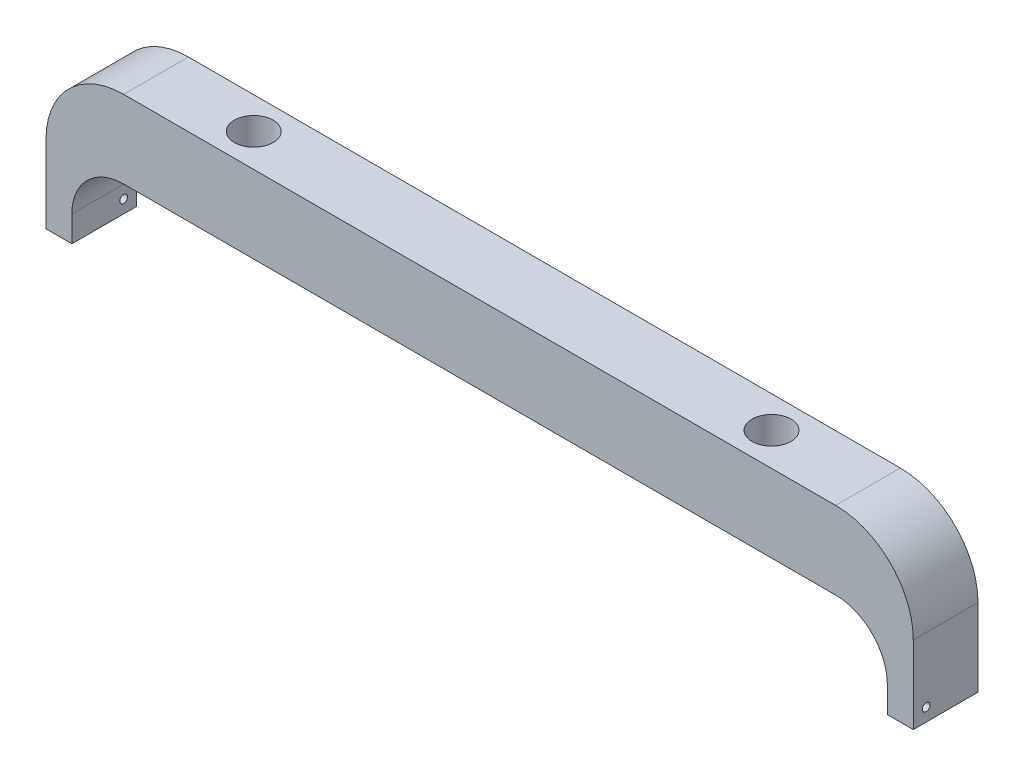
SolidWorks part; units mm, degrees
ref_plane "Front Plane" through (0, 0, 0) normal (0, 0, 1) x (1, 0, 0)
ref_plane "Top Plane" through (0, 0, 0) normal (0, 1, 0) x (1, 0, 0)
ref_plane "Right Plane" through (0, 0, 0) normal (1, 0, 0) x (0, 0, -1)
sketch "Sketch2" plane through (0, 0, 0) normal (0, 0, 1) x (1, 0, 0)
  line L0 (-27.5, 0) -> (-27.5, -6)
  line L1 (-27.5, 0) -> (27.5, 0)
  line L2 (-27.5, -6) -> (27.5, -6)
  line L3 (27.5, -6) -> (27.5, 0)
  line L4 (-33.5, -6) -> (-33.5, -12)
  line L5 (-33.5, -12) -> (-31.5, -12)
  line L6 (33.5, -6) -> (33.5, -12)
  line L7 (33.5, -12) -> (31.5, -12)
  line L8 (-31.5, -12) -> (-31.5, -10)
  line L10 (31.5, -12) -> (31.5, -10)
  arc A0 (-27.5, 0) -> (-33.5, -6) centre (-27.5, -6) ccw
  arc A1 (27.5, 0) -> (33.5, -6) centre (27.5, -6) cw
  arc A2 (-27.5, -6) -> (-31.5, -10) centre (-27.5, -10) ccw
  arc A3 (27.5, -6) -> (31.5, -10) centre (27.5, -10) cw
  dimension "D1" = 6
  dimension "D2" = 6
  dimension "D3" = 2
  dimension "D4" = 2
  dimension "D5" = 2
extrude "Boss-Extrude8" add sketch "Sketch2" along normal blind 5 contours L2 L3 L1 L0 | A2 L0 A0 L4 L5 L8 | L3 A3 L10 L7 L6 A1
sketch "Sketch4" plane through (33.5, 0, 0) normal (1, 0, 0) x (0, 0, -1)
  line L0 (-5, -12) -> (0, -12) construction
  line L1 (-5, -6) -> (-5, -12) construction
  circle A0 centre (-4, -11) radius 0.3
  dimension "D1" = 1
  dimension "D2" = 1
extrude "Cut-Extrude3" cut sketch "Sketch4" against normal blind 2
sketch "Sketch5" plane through (-33.5, 0, 0) normal (-1, 0, 0) x (0, 0, 1)
  line L1 (5, -12) -> (0, -12) construction
  circle A0 centre (1, -11) radius 0.3
  dimension "D2" = 1
extrude "Cut-Extrude4" cut sketch "Sketch5" against normal blind 2
sketch "Sketch6" plane through (0, 0, 0) normal (0, 1, 0) x (1, 0, 0)
  line L0 (-27.5, -2.5) -> (27.5, -2.5) construction
  line L1 (-27.5, -5) -> (-27.5, 0) construction
  line L2 (27.5, -5) -> (27.5, 0) construction
  line L3 (0, 0) -> (0, -5) construction
  line L4 (-27.5, -5) -> (27.5, -5) construction
  circle A0 centre (-20, -2.45) radius 1.5
  circle A1 centre (20, -2.45) radius 1.5
  dimension "D2" = 3
  dimension "D1" = 20
  dimension "D3" = 0.1
extrude "Cut-Extrude5" cut sketch "Sketch6" against normal blind 10
